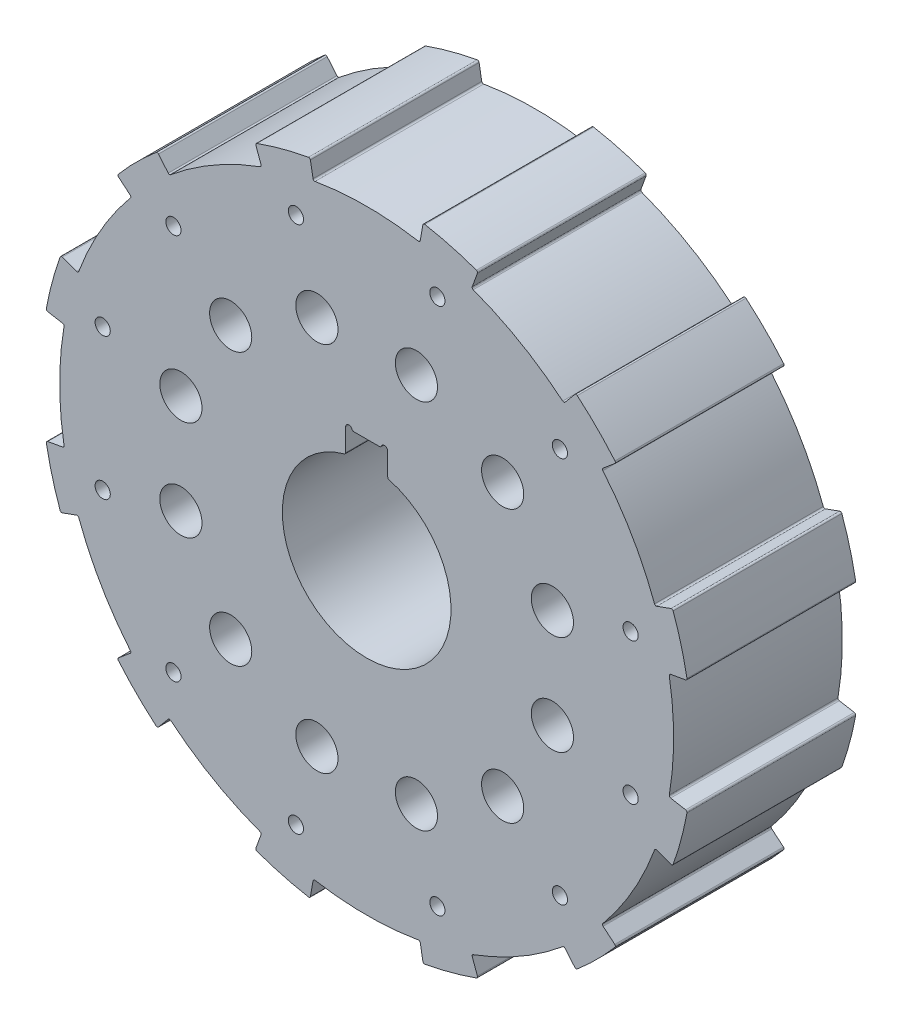
SolidWorks part; units mm, degrees
material "ABS"
ref_plane "Front Plane" through (0, 0, 0) normal (0, 0, 1) x (1, 0, 0)
ref_plane "Top Plane" through (0, 0, 0) normal (0, 1, 0) x (1, 0, 0)
ref_plane "Right Plane" through (0, 0, 0) normal (1, 0, 0) x (0, 0, -1)
sketch "Sketch1" plane through (0, 0, 0) normal (0, 0, 1) x (1, 0, 0)
  line L0 (0, 0) -> (50000, 0) construction
  line L1 (0, 0.6685) -> (0, 50000.6685) construction
  line L2 (0, 0) -> (-11.9647, 44.6528) construction
  line L3 (-1.9486, 15.8527) -> (1.9486, 15.8527)
  line L4 (-3.175, 15.8527) -> (-3.175, 12.4919)
  line L5 (-8.5126, 48.2772) -> (-8.0274, 45.5257)
  line L6 (3.175, 15.8527) -> (3.175, 12.4919)
  line L7 (-16.7665, 46.0656) -> (-15.8109, 43.4401)
  line L8 (8.5126, 48.2772) -> (8.0274, 45.5257)
  line L9 (16.7665, 46.0656) -> (15.8109, 43.4401)
  line L10 (31.5107, 37.553) -> (29.7148, 35.4127)
  line L11 (37.553, 31.5107) -> (35.4127, 29.7148)
  line L12 (46.0656, 16.7665) -> (43.4401, 15.8109)
  line L13 (48.2772, 8.5126) -> (45.5257, 8.0274)
  line L14 (48.2772, -8.5126) -> (45.5257, -8.0274)
  line L15 (46.0656, -16.7665) -> (43.4401, -15.8109)
  line L16 (37.553, -31.5107) -> (35.4127, -29.7148)
  line L17 (31.5107, -37.553) -> (29.7148, -35.4127)
  line L18 (16.7665, -46.0656) -> (15.8109, -43.4401)
  line L19 (8.5126, -48.2772) -> (8.0274, -45.5257)
  line L20 (-8.5126, -48.2772) -> (-8.0274, -45.5257)
  line L21 (-16.7665, -46.0656) -> (-15.8109, -43.4401)
  line L22 (-31.5107, -37.553) -> (-29.7148, -35.4127)
  line L23 (-37.553, -31.5107) -> (-35.4127, -29.7148)
  line L24 (-46.0656, -16.7665) -> (-43.4401, -15.8109)
  line L25 (-48.2772, -8.5126) -> (-45.5257, -8.0274)
  line L26 (-48.2772, 8.5126) -> (-45.5257, 8.0274)
  line L27 (-46.0656, 16.7665) -> (-43.4401, 15.8109)
  line L28 (-37.553, 31.5107) -> (-35.4127, 29.7148)
  line L29 (-31.5107, 37.553) -> (-29.7148, 35.4127)
  circle A0 centre (0, 0) radius 46.228 construction
  arc A1 (-3.3618, 12.247) -> (3.3618, 12.247) centre (0, 0) ccw
  arc A2 (-3.175, 15.8527) -> (-2.1881, 16.0221) centre (-2.667, 15.8527) cw
  arc A3 (-2.1881, 16.0221) -> (-1.9486, 15.8527) centre (-1.9486, 16.1067) ccw
  arc A4 (3.175, 15.8527) -> (2.1881, 16.0221) centre (2.667, 15.8527) ccw
  arc A5 (2.1881, 16.0221) -> (1.9486, 15.8527) centre (1.9486, 16.1067) cw
  arc A6 (3.175, 12.4919) -> (3.3618, 12.247) centre (3.429, 12.4919) ccw
  arc A7 (-3.175, 12.4919) -> (-3.3618, 12.247) centre (-3.429, 12.4919) cw
  circle A8 centre (-7.4944, 27.9693) radius 3.175
  circle A9 centre (7.4944, 27.9693) radius 3.175
  circle A10 centre (20.475, 20.475) radius 3.175
  circle A11 centre (27.9693, 7.4944) radius 3.175
  circle A12 centre (27.9693, -7.4944) radius 3.175
  circle A13 centre (20.475, -20.475) radius 3.175
  circle A14 centre (7.4944, -27.9693) radius 3.175
  circle A15 centre (-7.4944, -27.9693) radius 3.175
  circle A16 centre (-20.475, -20.475) radius 3.175
  circle A17 centre (-27.9693, -7.4944) radius 3.175
  circle A18 centre (-27.9693, 7.4944) radius 3.175
  circle A19 centre (-20.475, 20.475) radius 3.175
  circle A20 centre (-10.6499, 39.7459) radius 1.143
  circle A21 centre (10.6499, 39.7459) radius 1.143
  circle A22 centre (29.096, 29.096) radius 1.143
  circle A23 centre (39.7459, 10.6499) radius 1.143
  circle A24 centre (39.7459, -10.6499) radius 1.143
  circle A25 centre (29.096, -29.096) radius 1.143
  circle A26 centre (10.6499, -39.7459) radius 1.143
  circle A27 centre (-10.6499, -39.7459) radius 1.143
  circle A28 centre (-29.096, -29.096) radius 1.143
  circle A29 centre (-39.7459, -10.6499) radius 1.143
  circle A30 centre (-39.7459, 10.6499) radius 1.143
  circle A31 centre (-29.096, 29.096) radius 1.143
  arc A32 (-8.5126, 48.2772) -> (-16.7665, 46.0656) centre (0, 0) ccw
  arc A33 (-8.0274, 45.5257) -> (8.0274, 45.5257) centre (0, 0) cw
  arc A34 (16.7665, 46.0656) -> (8.5126, 48.2772) centre (0, 0) ccw
  arc A35 (15.8109, 43.4401) -> (29.7148, 35.4127) centre (0, 0) cw
  arc A36 (37.553, 31.5107) -> (31.5107, 37.553) centre (0, 0) ccw
  arc A37 (35.4127, 29.7148) -> (43.4401, 15.8109) centre (0, 0) cw
  arc A38 (48.2772, 8.5126) -> (46.0656, 16.7665) centre (0, 0) ccw
  arc A39 (45.5257, 8.0274) -> (45.5257, -8.0274) centre (0, 0) cw
  arc A40 (46.0656, -16.7665) -> (48.2772, -8.5126) centre (0, 0) ccw
  arc A41 (43.4401, -15.8109) -> (35.4127, -29.7148) centre (0, 0) cw
  arc A42 (31.5107, -37.553) -> (37.553, -31.5107) centre (0, 0) ccw
  arc A43 (29.7148, -35.4127) -> (15.8109, -43.4401) centre (0, 0) cw
  arc A44 (8.5126, -48.2772) -> (16.7665, -46.0656) centre (0, 0) ccw
  arc A45 (8.0274, -45.5257) -> (-8.0274, -45.5257) centre (0, 0) cw
  arc A46 (-16.7665, -46.0656) -> (-8.5126, -48.2772) centre (0, 0) ccw
  arc A47 (-15.8109, -43.4401) -> (-29.7148, -35.4127) centre (0, 0) cw
  arc A48 (-37.553, -31.5107) -> (-31.5107, -37.553) centre (0, 0) ccw
  arc A49 (-35.4127, -29.7148) -> (-43.4401, -15.8109) centre (0, 0) cw
  arc A50 (-48.2772, -8.5126) -> (-46.0656, -16.7665) centre (0, 0) ccw
  arc A51 (-45.5257, -8.0274) -> (-45.5257, 8.0274) centre (0, 0) cw
  arc A52 (-46.0656, 16.7665) -> (-48.2772, 8.5126) centre (0, 0) ccw
  arc A53 (-43.4401, 15.8109) -> (-35.4127, 29.7148) centre (0, 0) cw
  arc A54 (-31.5107, 37.553) -> (-37.553, 31.5107) centre (0, 0) ccw
  arc A55 (-29.7148, 35.4127) -> (-15.8109, 43.4401) centre (0, 0) cw
  point P17 (3.175, 12.2967)
  point P24 (-3.175, 12.2967)
  point P28 (0, 0)
  point P52 (0, 0)
  point P77 (0, 0)
  point P140 (0, 0)
  dimension "D2" = 25.4
  dimension "D5" = 0.508
  dimension "D6" = 0.254
  dimension "D7" = 0.254
  dimension "D8" = 6.35
  dimension "D11" = 2.286
  dimension "D14" = 98.044
  dimension "D16" = 92.456
  dimension "D3" = 6.35
  dimension "D4" = 3.556
  dimension "D9" = 28.956
  dimension "D12" = 41.148
  dimension "D15" = 10
  dimension "D10" = 12
  dimension "D13" = 12
  dimension "D17" = 12
extrude "Boss-Extrude1" add sketch "Sketch1" along normal blind 25.4
fillet "Fillet1" radius 0.254 48 edges at (15.8109, 43.4401, 12.7) (8.0274, 45.5257, 12.7) (16.7665, 46.0656, 12.7) (8.5126, 48.2772, 12.7) (43.4401, 15.8109, 12.7) (45.5257, 8.0274, 12.7) (48.2772, 8.5126, 12.7) (46.0656, 16.7665, 12.7) (37.553, 31.5107, 12.7) (35.4127, 29.7148, 12.7) (29.7148, 35.4127, 12.7) (31.5107, 37.553, 12.7) (48.2772, -8.5126, 12.7) (45.5257, -8.0274, 12.7) (43.4401, -15.8109, 12.7) (46.0656, -16.7665, 12.7) (35.4127, -29.7148, 12.7) (37.553, -31.5107, 12.7) (31.5107, -37.553, 12.7) (29.7148, -35.4127, 12.7) (16.7665, -46.0656, 12.7) (15.8109, -43.4401, 12.7) (-8.0274, -45.5257, 12.7) (8.5126, -48.2772, 12.7) (8.0274, -45.5257, 12.7) (-8.5126, -48.2772, 12.7) (-16.7665, -46.0656, 12.7) (-15.8109, -43.4401, 12.7) (-29.7148, -35.4127, 12.7) (-31.5107, -37.553, 12.7) (-37.553, -31.5107, 12.7) (-35.4127, -29.7148, 12.7) (-45.5257, -8.0274, 12.7) (-43.4401, -15.8109, 12.7) (-46.0656, -16.7665, 12.7) (-48.2772, -8.5126, 12.7) (-45.5257, 8.0274, 12.7) (-48.2772, 8.5126, 12.7) (-46.0656, 16.7665, 12.7) (-43.4401, 15.8109, 12.7) (-35.4127, 29.7148, 12.7) (-29.7148, 35.4127, 12.7) (-37.553, 31.5107, 12.7) (-31.5107, 37.553, 12.7) (-8.0274, 45.5257, 12.7) (-15.8109, 43.4401, 12.7) (-16.7665, 46.0656, 12.7) (-8.5126, 48.2772, 12.7)
